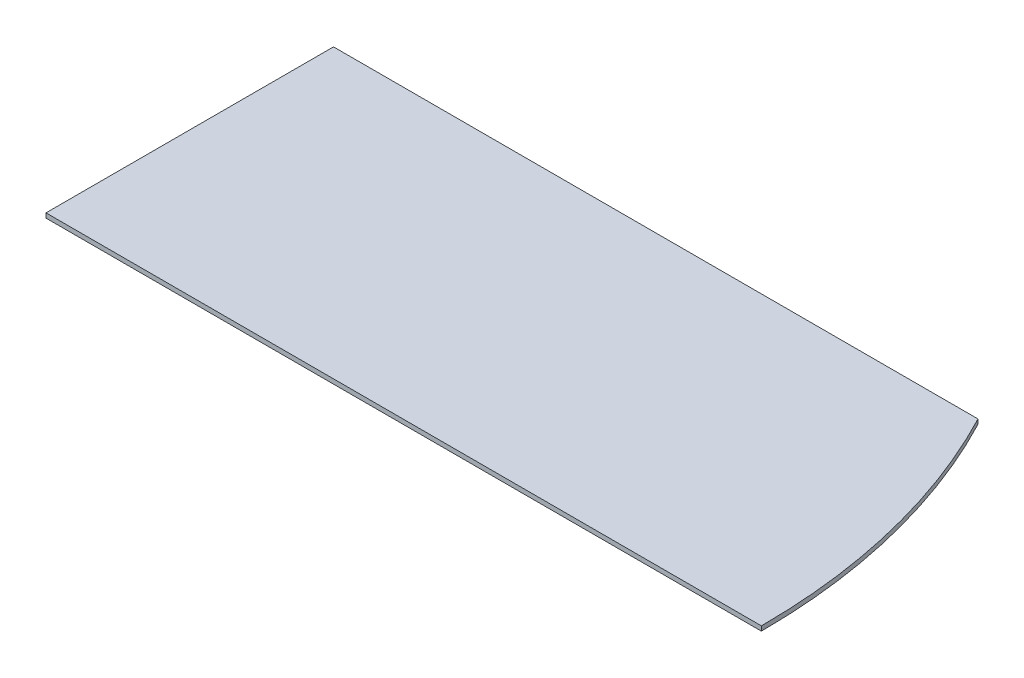
SolidWorks part; units mm, degrees
ref_plane "Front Plane" through (0, 0, 0) normal (0, 0, 1) x (1, 0, 0)
ref_plane "Top Plane" through (0, 0, 0) normal (0, 1, 0) x (1, 0, 0)
ref_plane "Right Plane" through (0, 0, 0) normal (1, 0, 0) x (0, 0, -1)
sketch "Sketch1" plane through (0, 0, 0) normal (0, 1, 0) x (1, 0, 0)
  line L1 (0, 0) -> (311, 0)
  line L2 (0, 0) -> (0, 125)
  line L3 (0, 125) -> (280.1932, 125)
  arc A0 (311, 0) -> (280.1932, 125) centre (42, 0) ccw
  point P1 (43.9915, -32.6724)
  point P7 (271.1276, 125)
  point P8 (0, 0)
  point P9 (43.9798, -32.5761)
  point P10 (43.9844, -32.614)
  point P11 (43.1529, -24.8782)
  dimension "D3" = 269
  dimension "D1" = 125
  dimension "D2" = 311
extrude "Boss-Extrude1" add sketch "Sketch1" along normal blind 2
